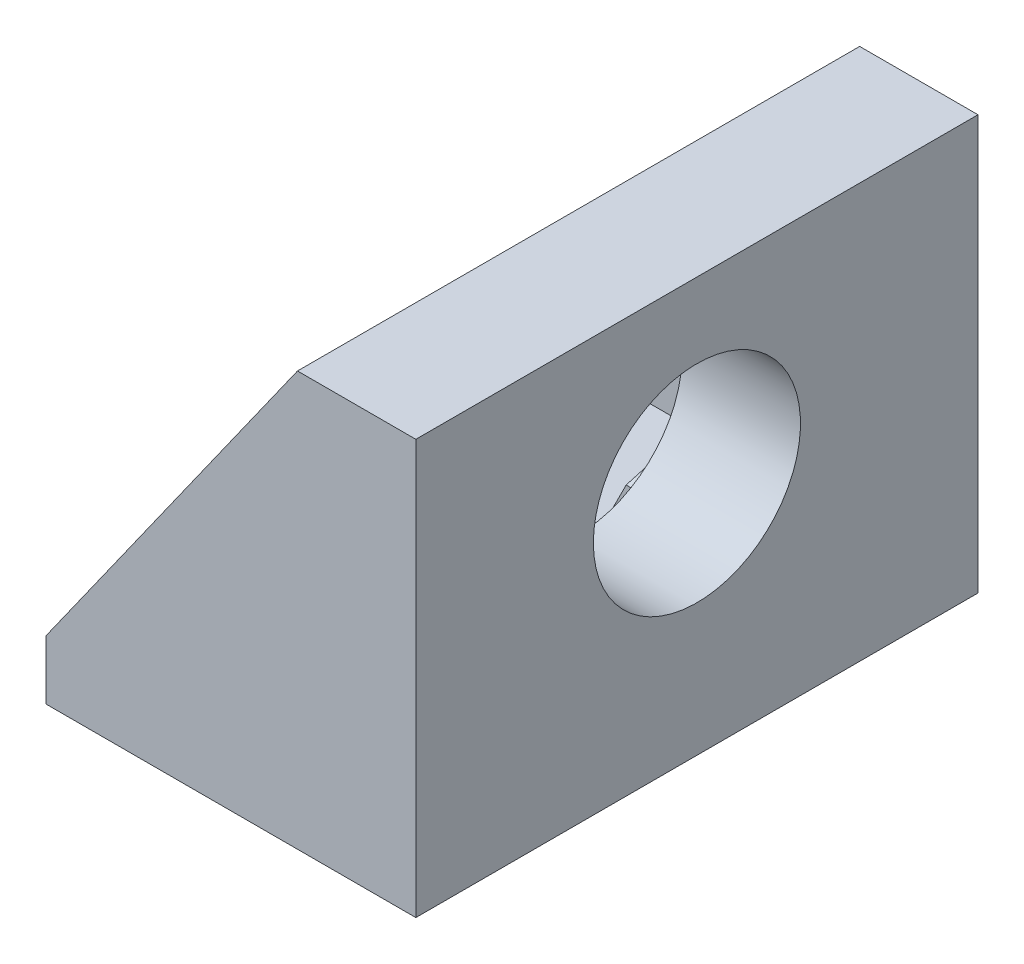
SolidWorks part; units mm, degrees
ref_plane "Front Plane" through (0, 0, 0) normal (0, 0, 1) x (1, 0, 0)
ref_plane "Top Plane" through (0, 0, 0) normal (0, 1, 0) x (1, 0, 0)
ref_plane "Right Plane" through (0, 0, 0) normal (1, 0, 0) x (0, 0, -1)
sketch "Sketch1" plane through (0, 0, 0) normal (0, 1, 0) x (1, 0, 0)
  line L0 (-6.25, -7.5) -> (6.25, -7.5)
  line L1 (-6.25, -7.5) -> (-6.25, 7.5)
  line L2 (6.25, -7.5) -> (6.25, 7.5)
  line L3 (-6.25, 7.5) -> (6.25, 7.5)
  line L4 (-6.25, -7.5) -> (6.25, 7.5) construction
  line L5 (6.25, -7.5) -> (-6.25, 7.5) construction
  point P1 (0, 0)
  dimension "D1" = 15
  dimension "D2" = 12.5
extrude "Boss-Extrude1" add sketch "Sketch1" along normal blind 2
sketch "Sketch4" plane through (0, 2, 0) normal (0, 1, 0) x (1, 0, 0)
  line L0 (6.25, 7.5) -> (6.25, -7.5)
  line L1 (6.25, 7.5) -> (2.25, 7.5)
  line L2 (6.25, -7.5) -> (2.25, -7.5)
  line L3 (2.25, 7.5) -> (2.25, -7.5)
  dimension "D1" = 4
extrude "Boss-Extrude2" add sketch "Sketch4" along normal blind 12
sketch "Sketch8" plane through (0, 0, 7.5) normal (0, 0, 1) x (1, 0, 0)
  line L0 (2.25, 2) -> (2.25, 7)
  line L1 (2.25, 14) -> (2.25, 2) construction
  line L2 (2.25, 7) -> (-0.25, 2)
  line L3 (-6.25, 2) -> (2.25, 2) construction
  line L4 (-0.25, 2) -> (2.25, 2)
  dimension "D1" = 5
  dimension "D2" = 2.5
extrude "Boss-Extrude3" add sketch "Sketch8" against normal blind 4
sketch "Sketch5" plane through (2.25, 0, 0) normal (-1, 0, 0) x (0, 0, 1)
  line L0 (7.5, 0) -> (-7.5, 0) construction
  circle A0 centre (0, 7.965) radius 3.5
  dimension "D1" = 7
  dimension "D2" = 7.965
extrude "Cut-Extrude2" cut sketch "Sketch5" against normal through all
hole_wizard "CSK for #6 Flat Head Machine Screw (100)1" positions "Sketch11" profile "Sketch10" countersink size "#6" standard "ANSI Inch" end condition through all
sketch "Sketch11" plane through (0, 2, 0) normal (0, 1, 0) x (1, 0, 0)
  line L0 (-6.25, 7.5) -> (-6.25, -7.5) construction
  line L1 (-6.25, -7.5) -> (-0.25, -7.5) construction
  point P0 (-2.25, 0)
  dimension "D1" = 4
  dimension "D2" = 7.5
sketch "Sketch10" plane through (-2.25, 2, 0) normal (1, 0, 0) x (0, 0, 1)
  line L0 (0, 0) -> (0, 2)
  line L1 (0, 2) -> (2.1526, 2)
  line L2 (2.1526, 2) -> (2.1526, 1.1669)
  line L3 (2.1526, 1.1669) -> (3.5433, 0)
  line L5 (3.5433, 0) -> (0, 0)
  line L6 (-2.1526, 1.1669) -> (-3.5433, 0) construction
  line L11 (0, -6.35) -> (0, 107.95) construction
  dimension "Thru Hole Dia." = 4.3053
  dimension "Thru Hole Depth" = 2
  dimension "Near C'Sink Dia." = 7.0866
  dimension "Near C'Sink Angle" = 100
sketch "Sketch7" plane through (0, 0, 0) normal (0, -1, 0) x (1, 0, 0)
  line L0 (-6.25, -7.5) -> (-6.25, 7.5) construction
  circle A0 centre (-2.25, 0) radius 2.25
  dimension "D1" = 4.5
  dimension "D2" = 4
extrude "Cut-Extrude3" [suppressed] cut sketch "Sketch7" against normal through all
sketch "Sketch9" plane through (2.25, 0, 0) normal (-1, 0, 0) x (0, 0, 1)
  circle A2 centre (0, 7.965) radius 5.9
  circle A3 centre (0, 7.965) radius 5.9
  dimension "D1" = 2.4
mirror "Mirror1" about plane through (0, 0, 0) normal (0, 0, 1) of "Boss-Extrude3"
extrude "Cut-Extrude4" cut sketch "Sketch9" along normal blind 3
sketch "Sketch12" plane through (0, 0, 7.5) normal (0, 0, 1) x (1, 0, 0)
  line L0 (2.25, 14) -> (-6.25, 2)
  line L7 (-6.25, 0) -> (6.25, 0)
  line L8 (6.25, 0) -> (6.25, 14)
  line L9 (6.25, 14) -> (2.25, 14)
  line L10 (2.25, 14) -> (2.25, 7)
  line L11 (2.25, 7) -> (-0.25, 2)
  line L12 (-0.25, 2) -> (-6.25, 2)
  line L13 (-6.25, 2) -> (-6.25, 0)
  line L14 (-6.25, 0) -> (6.25, 0)
  line L15 (6.25, 0) -> (6.25, 14)
  line L16 (6.25, 14) -> (2.25, 14)
  line L20 (-6.25, 2) -> (-6.25, 0)
  dimension "D1" = 0
extrude "Boss-Extrude4" add sketch "Sketch12" along normal blind 2
mirror "Mirror2" about plane through (0, 0, 0) normal (0, 0, 1) of "Boss-Extrude4"
